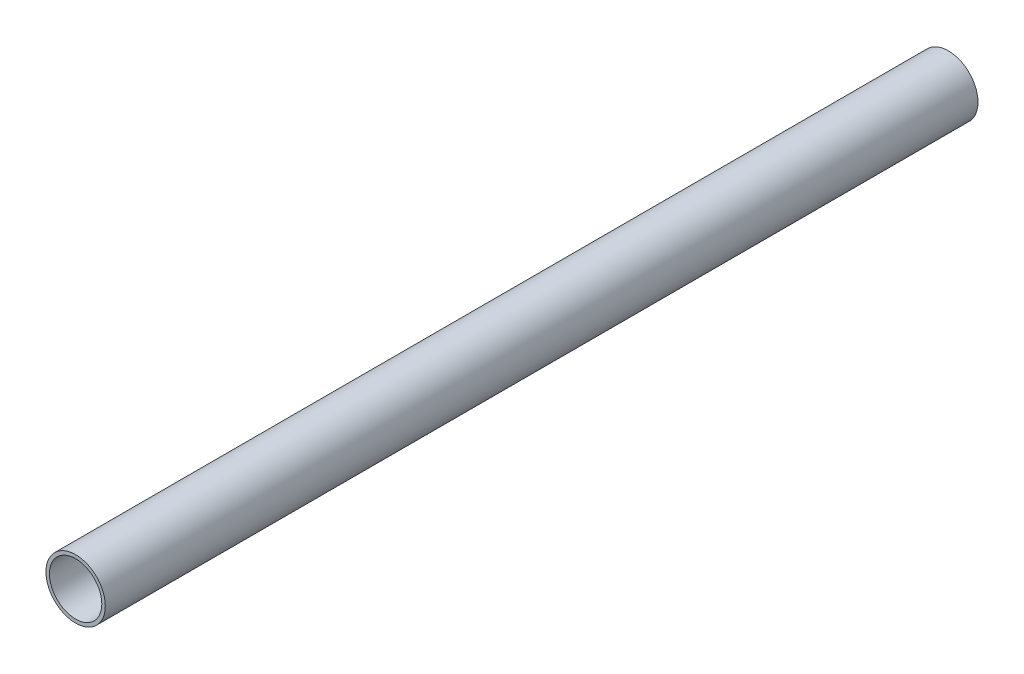
SolidWorks part; units mm, degrees
ref_plane "Front Plane" through (0, 0, 0) normal (0, 0, 1) x (1, 0, 0)
ref_plane "Top Plane" through (0, 0, 0) normal (0, 1, 0) x (1, 0, 0)
ref_plane "Right Plane" through (0, 0, 0) normal (1, 0, 0) x (0, 0, -1)
sketch "Sketch1" plane through (0, 0, 0) normal (0, 0, 1) x (1, 0, 0)
  circle A0 centre (0, 0) radius 17
  circle A1 centre (0, 0) radius 15
  dimension "D1" = 34
  dimension "D2" = 30
extrude "Boss-Extrude1" add sketch "Sketch1" along normal blind 500
